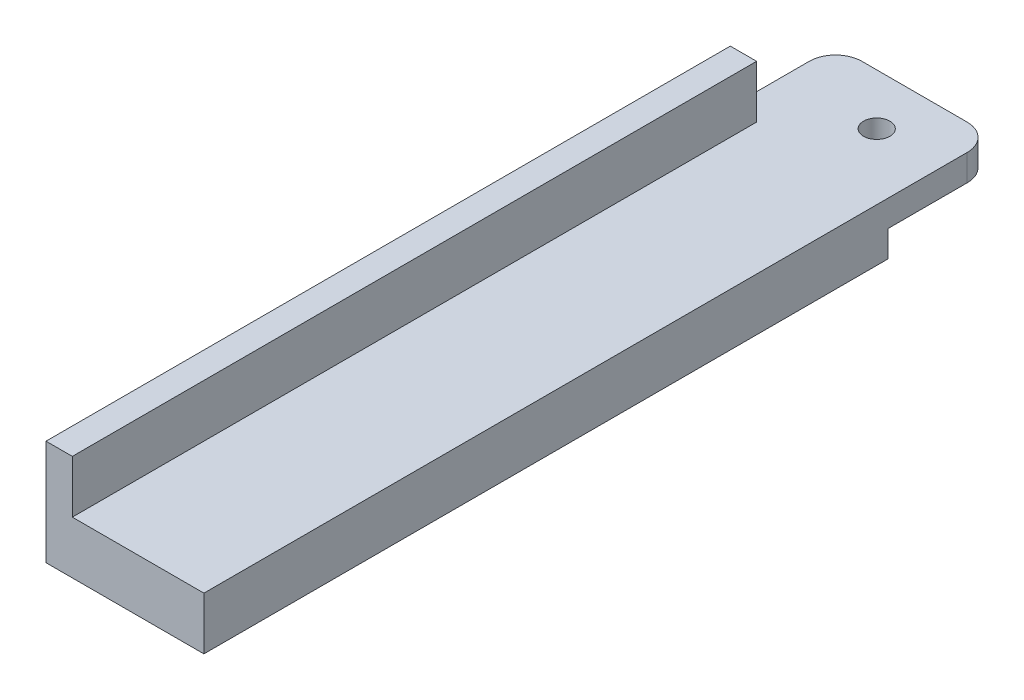
SolidWorks part; units mm, degrees
material "3.0205 (EN-AW 1200)"
ref_plane "前视基准面" through (0, 0, 0) normal (0, 0, 1) x (1, 0, 0)
ref_plane "上视基准面" through (0, 0, 0) normal (0, 1, 0) x (1, 0, 0)
ref_plane "右视基准面" through (0, 0, 0) normal (1, 0, 0) x (0, 0, -1)
other "Configuration Table"
sketch "草图1" plane through (0, 0, 0) normal (0, 0, 1) x (1, 0, 0)
  line L0 (0, 0) -> (0, -40)
  line L1 (0, -40) -> (60, -40)
  line L5 (10, 0) -> (0, 0)
  line L10 (60, -40) -> (60, -20)
  line L11 (60, -20) -> (10, -20)
  line L12 (10, -20) -> (10, 0)
  dimension "D4" = 40
extrude "凸台-拉伸1" add sketch "草图1" along normal blind 300
sketch "草图2" plane through (0, 0, 0) normal (0, 0, -1) x (-1, 0, 0)
  line L7 (-10, -20) -> (0, -20)
  line L8 (0, 0) -> (0, -40) construction
  line L9 (0, -20) -> (0, 0)
  line L10 (0, 0) -> (-10, 0)
  line L12 (-10, -30) -> (0, -30)
  line L13 (0, -30) -> (0, -40)
  line L14 (0, -40) -> (-10, -40)
  line L19 (-10, -30) -> (-60, -30)
  line L20 (-60, -30) -> (-60, -40)
  line L21 (-60, -40) -> (-10, -40)
  line L22 (-10, 0) -> (-10, -20)
extrude "切除-拉伸1" cut sketch "草图2" against normal blind 40
sketch "草图4" plane through (0, -20, 0) normal (0, 1, 0) x (1, 0, 0)
  circle A2 centre (35, -19.3649) radius 5
extrude "切除-拉伸2" cut sketch "草图4" against normal through all both
fillet "圆角1" radius 10 2 edges at (0, -25, 0) (60, -25, 0)
